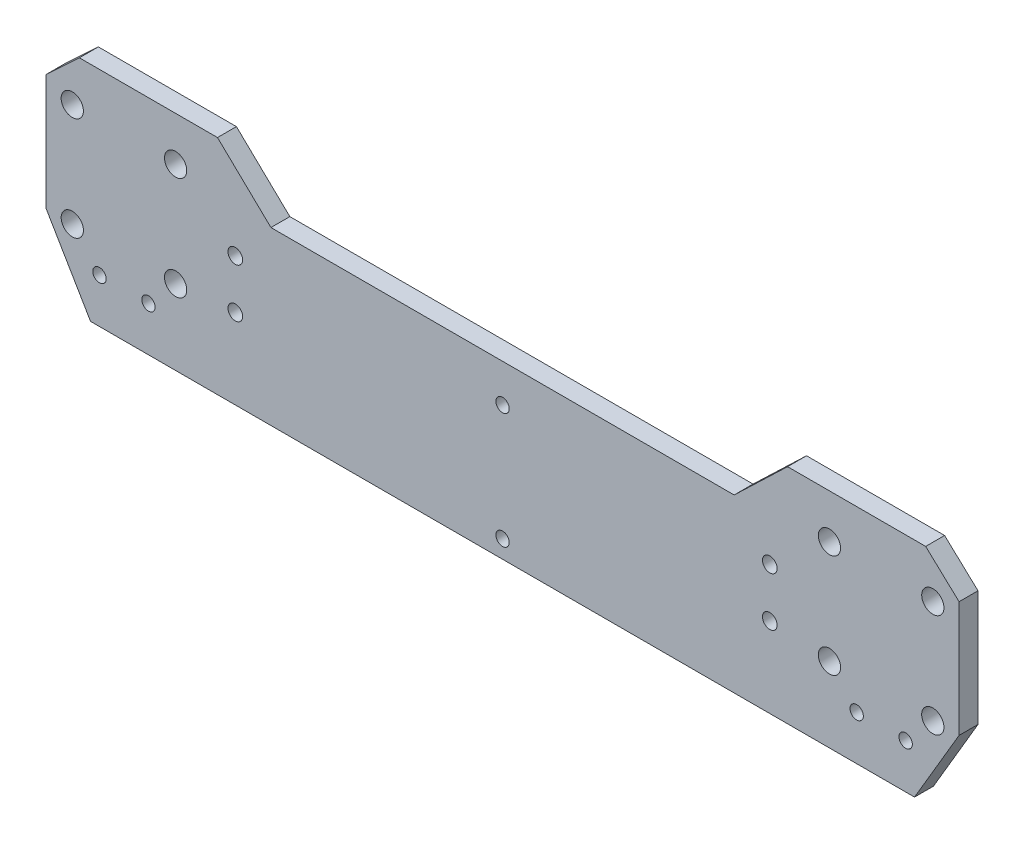
SolidWorks part; units mm, degrees
material "6063-O, Extruded Rod (SS)"
ref_plane "Front Plane" through (0, 0, 0) normal (0, 0, 1) x (1, 0, 0)
ref_plane "Top Plane" through (0, 0, 0) normal (0, 1, 0) x (1, 0, 0)
ref_plane "Right Plane" through (0, 0, 0) normal (1, 0, 0) x (0, 0, -1)
sketch "Sketch1" plane through (0, 0, 0) normal (0, 0, 1) x (1, 0, 0)
  line L0 (102.5, -33) -> (102.5, -7)
  line L1 (102.5, -7) -> (95, 0)
  line L2 (95, 0) -> (64, 0)
  line L3 (64, 0) -> (52, -11.5)
  line L4 (52, -11.5) -> (-52, -11.5)
  line L5 (-52, -11.5) -> (-64, 0)
  line L6 (-64, 0) -> (-95, 0)
  line L7 (-95, 0) -> (-102.5, -7)
  line L8 (-102.5, -7) -> (-102.5, -33)
  line L9 (-102.5, -33) -> (-92.5, -50)
  line L10 (-92.5, -50) -> (92.5, -50)
  line L11 (92.5, -50) -> (102.5, -33)
  line L552 (0.0033, -46.0075) -> (0.0033, -20.0075) construction
  circle A0 centre (-96.6, -9.9) radius 2.5
  circle A1 centre (-73.4, -9.9) radius 2.5
  circle A2 centre (-60, -21) radius 1.65
  circle A3 centre (-60, -32) radius 1.65
  circle A4 centre (-73.3987, -33.1125) radius 2.4987
  circle A5 centre (-96.597, -33.1134) radius 2.4999
  circle A6 centre (-90.5, -40) radius 1.5
  circle A7 centre (-79.5, -40) radius 1.5
  circle A8 centre (0.0033, -20.0075) radius 1.5
  circle A9 centre (0.0033, -46.0075) radius 1.5
  circle A18 centre (96.6066, -9.8997) radius 2.5
  circle A19 centre (96.6037, -33.1131) radius 2.4999
  circle A20 centre (90.5067, -39.9998) radius 1.5
  circle A21 centre (73.4066, -9.8998) radius 2.5
  circle A22 centre (79.5067, -39.9998) radius 1.5
  circle A23 centre (73.4054, -33.1123) radius 2.4987
  circle A24 centre (60.0066, -20.9998) radius 1.65
  circle A25 centre (60.0066, -31.9999) radius 1.65
extrude "Boss-Extrude1" add sketch "Sketch1" along normal blind 4.25
